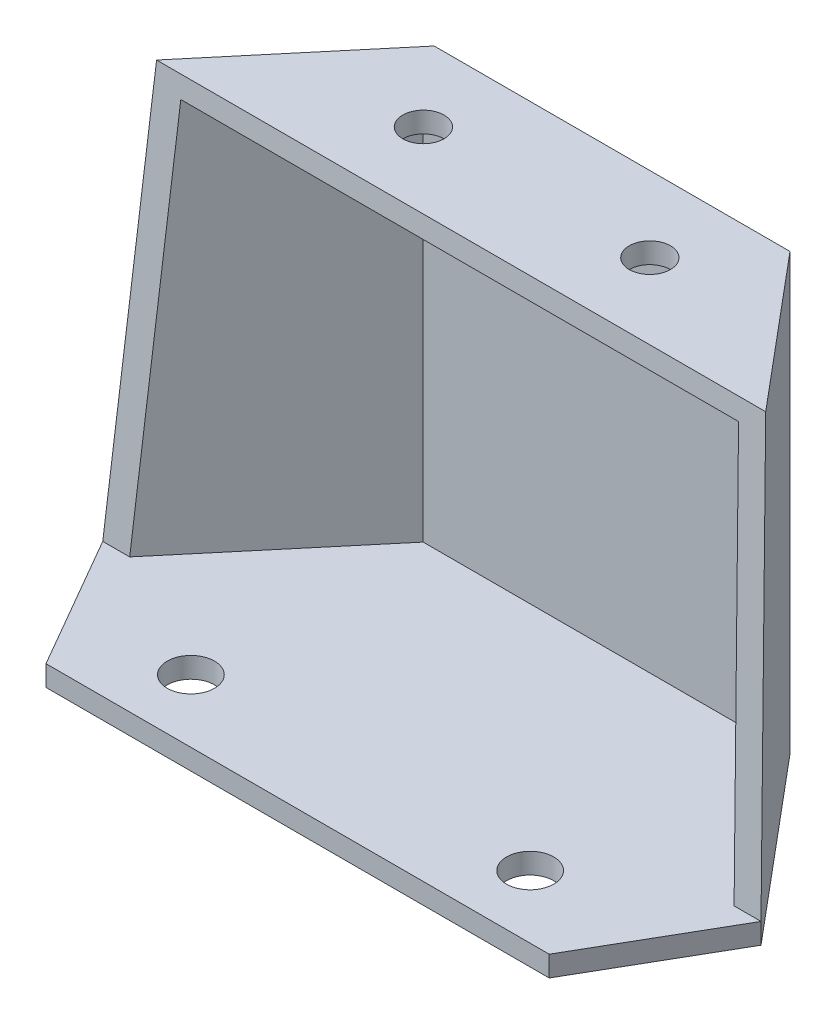
SolidWorks part; units mm, degrees
ref_plane "前视基准面" through (0, 0, 0) normal (0, 0, 1) x (1, 0, 0)
ref_plane "上视基准面" through (0, 0, 0) normal (0, 1, 0) x (1, 0, 0)
ref_plane "右视基准面" through (0, 0, 0) normal (1, 0, 0) x (0, 0, -1)
sketch "草图1" plane through (0, 0, 0) normal (0, 1, 0) x (1, 0, 0)
  line L0 (0, 0) -> (0, 152.5) construction
  line L1 (122, 0) -> (-122, 0)
  line L2 (-122, 0) -> (-159.5924, 65.1119)
  line L3 (-159.5924, 65.1119) -> (-86.265, 152.5)
  line L4 (-86.265, 152.5) -> (86.265, 152.5)
  line L5 (159.5924, 65.1119) -> (86.265, 152.5)
  line L6 (122, 0) -> (159.5924, 65.1119)
  point P3 (0, 135.2475)
  dimension "D1" = 244
  dimension "D2" = 30
  dimension "D3" = 40
  dimension "D4" = 152.5
  dimension "D5" = 172.53
extrude "凸台-拉伸1" add sketch "草图1" along normal blind 211
shell "抽壳1" thickness 10
sketch "草图2" plane through (0, 0, 0) normal (1, 0, 0) x (0, 0, -1)
  line L0 (79.3, 211) -> (65.1119, 10)
  line L1 (65.1119, 211) -> (152.5, 211) construction
  line L2 (65.1119, 211) -> (65.1119, 0) construction
  line L3 (79.3, 211) -> (0, 211)
  line L4 (0, 211) -> (0, 10)
  line L5 (0, 211) -> (0, 0) construction
  line L6 (0, 10) -> (65.1119, 10)
  dimension "D1" = 10
  dimension "D2" = 73.2
extrude "切除-拉伸1" cut sketch "草图2" against normal through all both and the other way through all
sketch "草图3" plane through (0, 211, 0) normal (0, 1, 0) x (1, 0, 0)
  line L0 (0, 0) -> (0, 152.5) construction
  line L1 (86.265, 152.5) -> (-86.265, 152.5) construction
  circle A0 centre (-54.9, 115.9) radius 10
  circle A1 centre (54.9, 115.9) radius 10
  point P9 (0, 0)
  point P10 (56.5317, 115.9)
  point P11 (52.9323, 115.9)
  point P12 (56.9551, 115.9)
  dimension "D1" = 20
  dimension "D2" = 20
  dimension "D3" = 109.8
  dimension "D4" = 36.6
  dimension "D5" = 54.9
extrude "切除-拉伸2" cut sketch "草图3" against normal blind 40 and the other way through all
sketch "草图4" plane through (0, 10, 0) normal (0, 1, 0) x (1, 0, 0)
  line L0 (0, 0) -> (0, 79.3) construction
  line L1 (-147.6871, 79.3) -> (147.6871, 79.3) construction
  line L2 (-122, 0) -> (122, 0) construction
  circle A0 centre (-82.25, 30.5) radius 11.451
  circle A1 centre (82.25, 30.5) radius 11.451
  dimension "D1" = 30.5
  dimension "D2" = 164.5
extrude "切除-拉伸3" cut sketch "草图4" against normal blind 40
